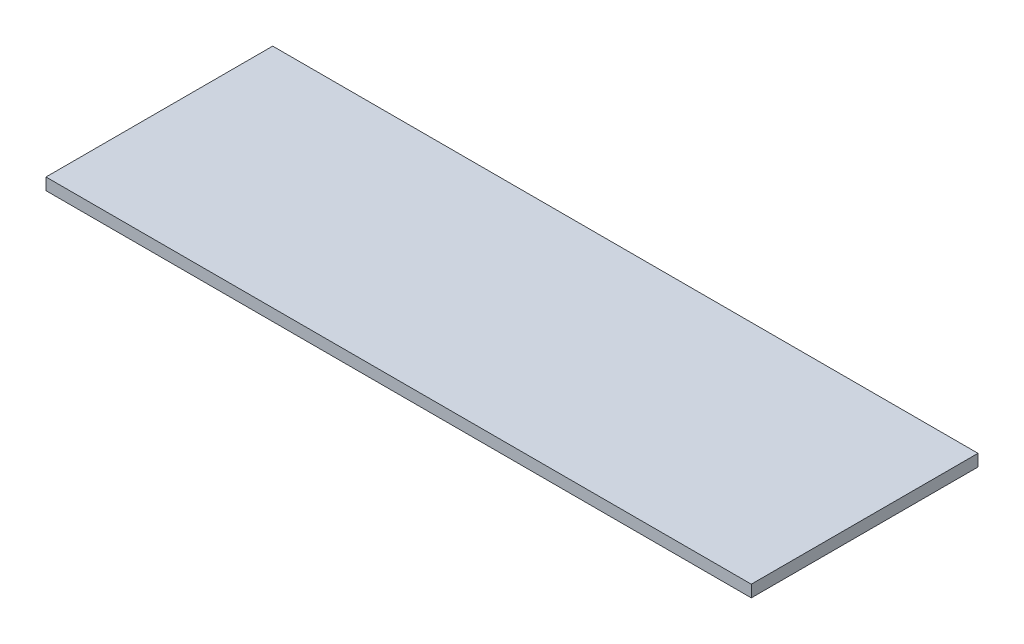
SolidWorks part; units mm, degrees
ref_plane "Front Plane" through (0, 0, 0) normal (0, 0, 1) x (1, 0, 0)
ref_plane "Top Plane" through (0, 0, 0) normal (0, 1, 0) x (1, 0, 0)
ref_plane "Right Plane" through (0, 0, 0) normal (1, 0, 0) x (0, 0, -1)
sketch "Sketch1" plane through (0, 0, 0) normal (0, 1, 0) x (1, 0, 0)
  line L1 (0, 0) -> (177.8, 0)
  line L2 (0, 0) -> (0, 57.15)
  line L3 (0, 57.15) -> (177.8, 57.15)
  line L4 (177.8, 0) -> (177.8, 57.15)
  dimension "D1" = 57.15
  dimension "D2" = 177.8
extrude "Boss-Extrude1" add sketch "Sketch1" along normal blind 3
